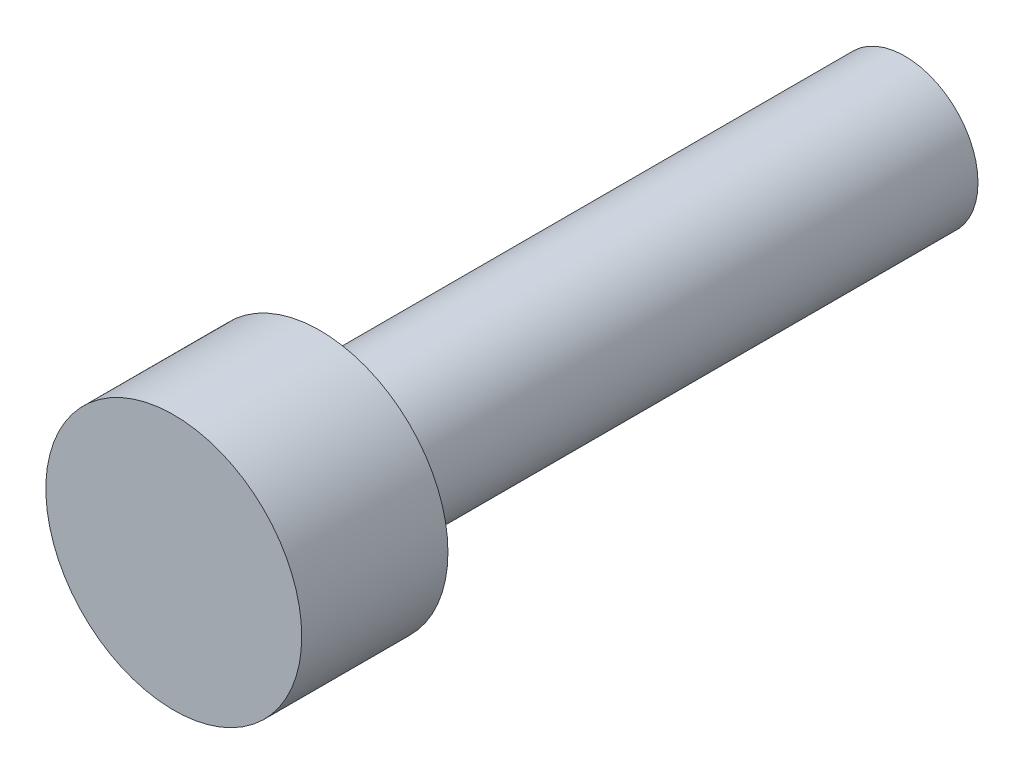
SolidWorks part; units mm, degrees
ref_plane "前视基准面" through (0, 0, 0) normal (0, 0, 1) x (1, 0, 0)
ref_plane "上视基准面" through (0, 0, 0) normal (0, 1, 0) x (1, 0, 0)
ref_plane "右视基准面" through (0, 0, 0) normal (1, 0, 0) x (0, 0, -1)
other "Configuration Table"
sketch "Sketch_Nominal_shank" plane through (0, 0, 0) normal (0, 0, 1) x (1, 0, 0)
  circle A0 centre (0, 0) radius 2
  dimension "D1" = 4
extrude "Nominal_shank" add sketch "Sketch_Nominal_shank" along normal blind 16 from offset 16
sketch "Sketch_Head" plane through (0, 0, 0) normal (0, 0, 1) x (1, 0, 0)
  circle A0 centre (0, 0) radius 3.5
  dimension "D1" = 7
extrude "Head" add sketch "Sketch_Head" along normal blind 4 from offset 0
